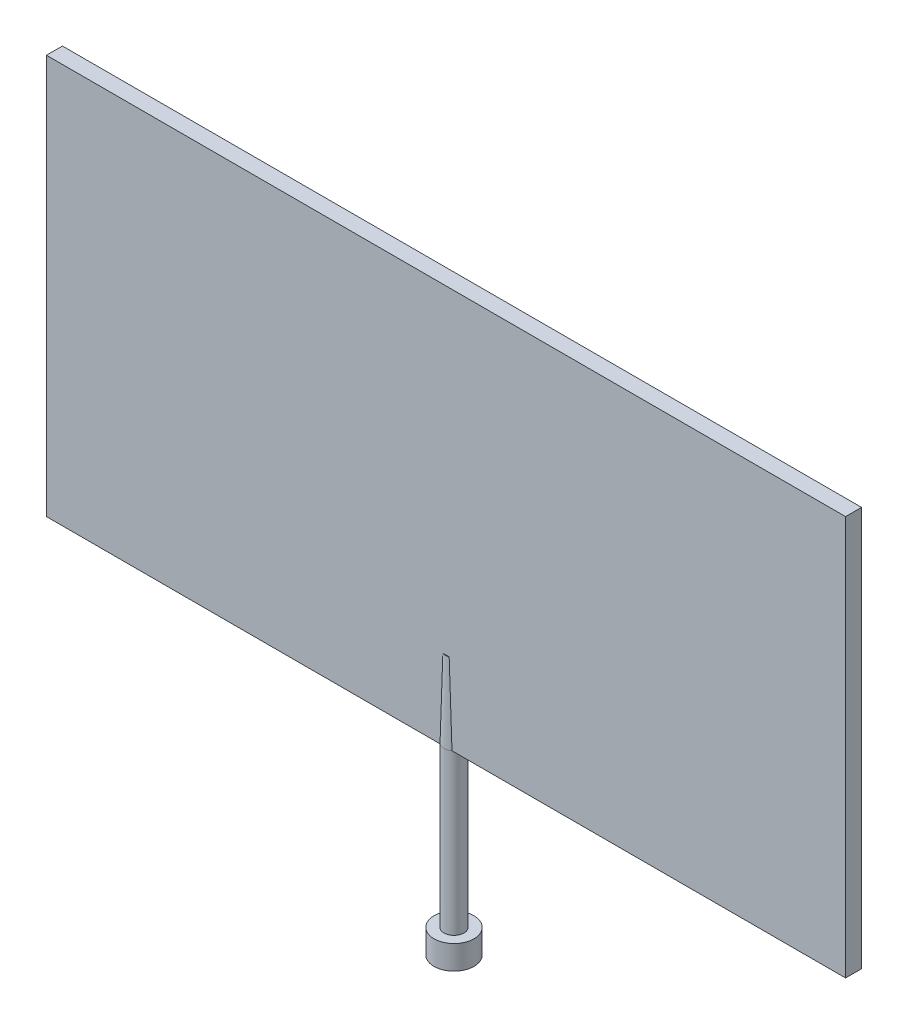
SolidWorks part; units mm, degrees
ref_plane "Front Plane" through (0, 0, 0) normal (0, 0, 1) x (1, 0, 0)
ref_plane "Top Plane" through (0, 0, 0) normal (0, 1, 0) x (1, 0, 0)
ref_plane "Right Plane" through (0, 0, 0) normal (1, 0, 0) x (0, 0, -1)
sketch "Sketch1" plane through (0, 0, 0) normal (0, 1, 0) x (1, 0, 0)
  line L1 (-76.25, 14.375) -> (23.75, 14.375)
  line L2 (-76.25, 14.375) -> (-76.25, 12.375)
  line L3 (-76.25, 12.375) -> (23.75, 12.375)
  line L4 (23.75, 14.375) -> (23.75, 12.375)
  dimension "D1" = 2
  dimension "D2" = 100
extrude "Boss-Extrude1" add sketch "Sketch1" along normal blind 50
sketch "Sketch2" plane through (0, 0, 0) normal (0, -1, 0) x (1, 0, 0)
  line L0 (-76.25, -13.375) -> (23.75, -13.375) construction
  line L1 (-76.25, -14.375) -> (-76.25, -12.375) construction
  line L2 (23.75, -12.375) -> (23.75, -14.375) construction
  line L3 (-26.25, -12.375) -> (-26.25, -14.375) construction
  line L4 (-76.25, -12.375) -> (23.75, -12.375) construction
  line L5 (23.75, -14.375) -> (-76.25, -14.375) construction
  circle A0 centre (-26.25, -13.375) radius 1.25
  dimension "D1" = 2.5
extrude "Boss-Extrude2" add sketch "Sketch2" against normal blind 10 draft 1
sketch "Sketch3" plane through (0, 0, 0) normal (0, -1, 0) x (1, 0, 0)
  circle A1 centre (-26.25, -13.375) radius 1.25
extrude "Boss-Extrude3" add sketch "Sketch3" along normal blind 20
sketch "Sketch4" plane through (0, -20, 0) normal (0, -1, 0) x (1, 0, 0)
  circle A0 centre (-26.25, -13.375) radius 2.499
  circle A1 centre (-26.25, -13.375) radius 1.25 construction
  circle A2 centre (-26.25, -13.375) radius 1.25
extrude "Boss-Extrude4" add sketch "Sketch4" along normal blind 3 separate body
